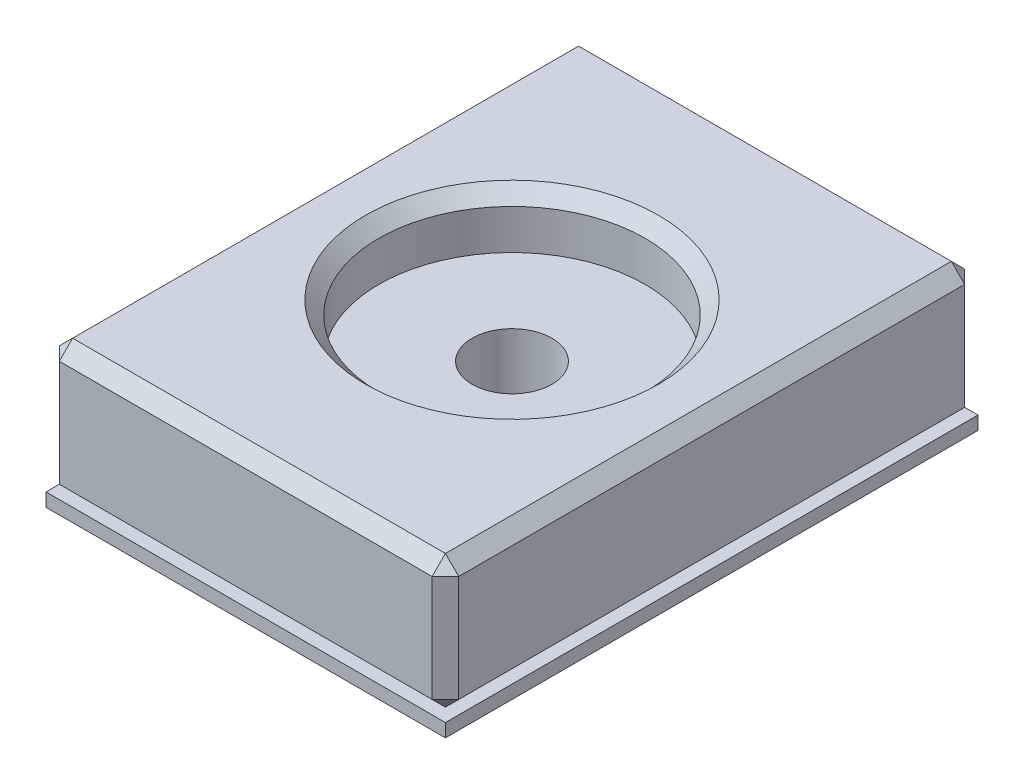
SolidWorks part; units mm, degrees
material "Cedro"
ref_plane "Alzado" through (0, 0, 0) normal (0, 0, 1) x (1, 0, 0)
ref_plane "Planta" through (0, 0, 0) normal (0, 1, 0) x (1, 0, 0)
ref_plane "Vista lateral" through (0, 0, 0) normal (1, 0, 0) x (0, 0, -1)
sketch "Croquis1" plane through (0, 0, 0) normal (0, 0, 1) x (1, 0, 0)
  line L1 (-7.5, -2.5) -> (7.5, -2.5)
  line L2 (-7.5, -2.5) -> (-7.5, 2.5)
  line L3 (-7.5, 2.5) -> (7.5, 2.5)
  line L4 (7.5, -2.5) -> (7.5, 2.5)
  line L5 (-7.5, -2.5) -> (7.5, 2.5) construction
  line L6 (-7.5, 2.5) -> (7.5, -2.5) construction
  point P0 (0, 0)
  dimension "D1" = 5
  dimension "D2" = 15
extrude "Saliente-Extruir1" add sketch "Croquis1" along normal mid plane 20
sketch "Croquis2" plane through (0, 2.5, 0) normal (0, 1, 0) x (1, 0, 0)
  circle A0 centre (0, 0) radius 1.5
  dimension "D1" = 3
extrude "Cortar-Extruir1" cut sketch "Croquis2" against normal through all
sketch "Croquis7" plane through (0, 2.5, 0) normal (0, 1, 0) x (1, 0, 0)
  circle A0 centre (0, 0) radius 5
  circle A1 centre (0, 0) radius 1.5 construction
  dimension "D1" = 10
extrude "Cortar-Extruir3" cut sketch "Croquis7" against normal blind 2
sketch "Croquis3" plane through (0, 0.5, 0) normal (0, 1, 0) x (1, 0, 0)
  line L0 (4, 0) -> (3.4641, 0) construction
  line L1 (-1.7321, -3) -> (1.7321, -3)
  line L2 (1.7321, -3) -> (3.4641, 0)
  line L3 (3.4641, 0) -> (1.7321, 3)
  line L4 (1.7321, 3) -> (-1.7321, 3)
  line L5 (-1.7321, 3) -> (-3.4641, 0)
  line L6 (-3.4641, 0) -> (-1.7321, -3)
  circle A0 centre (0, 0) radius 4
  circle A1 centre (0, 0) radius 3 construction
  dimension "D1" = 3
  dimension "D2" = 8
extrude "Saliente-Extruir2" add sketch "Croquis3" along normal blind 3 separate body
sketch "Croquis4" plane through (0, 3.5, 0) normal (0, 1, 0) x (1, 0, 0)
  circle A0 centre (0, 0) radius 4 construction
  circle A1 centre (0, 0) radius 4
extrude "Saliente-Extruir3" add sketch "Croquis4" along normal blind 6 draft 33
sketch "Croquis5" plane through (0, 9.5, 0) normal (0, 1, 0) x (1, 0, 0)
  line L0 (0, 0) -> (-2.75, 0) construction
  line L1 (0, 0) -> (-2.6027, -0.8879) construction
  line L2 (-2.6027, -0.8879) -> (-1.7264, -0.2864)
  line L3 (-1.7264, -0.2864) -> (-2.75, 0)
  line L4 (-1.7264, -0.2864) -> (0, 0) construction
  line L5 (-2.75, 0) -> (-2.6027, -0.8879) construction
  line L6 (-2.6764, -0.4439) -> (-1.7264, -0.2864)
  line L7 (-1.6936, 0.4406) -> (-2.5123, 1.1185)
  line L8 (-2.7388, 0.2475) -> (-1.6936, 0.4406)
  line L9 (-1.368, 1.0914) -> (-1.8401, 2.0436)
  line L10 (-2.4014, 1.3401) -> (-1.368, 1.0914)
  line L11 (-0.8058, 1.5534) -> (-0.8498, 2.6154)
  line L12 (-1.6487, 2.201) -> (-0.8058, 1.5534)
  line L13 (-0.1043, 1.7469) -> (0.2875, 2.7349)
  line L14 (-0.6109, 2.6813) -> (-0.1043, 1.7469)
  line L15 (0.6152, 1.6383) -> (1.375, 2.3816)
  line L16 (0.5324, 2.698) -> (0.6152, 1.6383)
  line L17 (1.2284, 1.2464) -> (2.2248, 1.6164)
  line L18 (1.5838, 2.2481) -> (1.2284, 1.2464)
  line L19 (1.6291, 0.639) -> (2.6899, 0.5718)
  line L20 (2.3613, 1.4096) -> (1.6291, 0.639)
  line L21 (1.7482, -0.0788) -> (2.6899, -0.5718)
  line L22 (2.7304, 0.3273) -> (1.7482, -0.0788)
  line L23 (1.565, -0.7831) -> (2.2248, -1.6164)
  line L24 (2.6275, -0.8115) -> (1.565, -0.7831)
  line L25 (1.1112, -1.3519) -> (1.375, -2.3816)
  line L26 (2.0703, -1.8101) -> (1.1112, -1.3519)
  line L27 (0.4653, -1.687) -> (0.2875, -2.7349)
  line L28 (1.1551, -2.4957) -> (0.4653, -1.687)
  line L29 (-0.2611, -1.7304) -> (-0.8498, -2.6154)
  line L30 (0.0401, -2.7497) -> (-0.2611, -1.7304)
  line L31 (-0.9424, -1.4746) -> (-1.8401, -2.0436)
  line L32 (-1.0817, -2.5283) -> (-0.9424, -1.4746)
  line L33 (-1.4607, -0.9638) -> (-2.5123, -1.1185)
  line L34 (-2.0166, -1.8697) -> (-1.4607, -0.9638)
  arc A0 (-2.7388, 0.2475) -> (-2.75, 0) centre (0, 0) ccw
  circle A1 centre (0, 0) radius 0.1036 construction
  arc A2 (-2.4014, 1.3401) -> (-2.5123, 1.1185) centre (0, 0) ccw
  arc A3 (-2.0166, -1.8697) -> (-1.8401, -2.0436) centre (0, 0) ccw
  arc A4 (-2.6027, -0.8879) -> (-2.5123, -1.1185) centre (0, 0) ccw
  arc A5 (-1.0817, -2.5283) -> (-0.8498, -2.6154) centre (0, 0) ccw
  arc A6 (0.0401, -2.7497) -> (0.2875, -2.7349) centre (0, 0) ccw
  arc A7 (1.1551, -2.4957) -> (1.375, -2.3816) centre (0, 0) ccw
  arc A8 (2.0703, -1.8101) -> (2.2248, -1.6164) centre (0, 0) ccw
  arc A9 (2.6275, -0.8115) -> (2.6899, -0.5718) centre (0, 0) ccw
  arc A10 (2.7304, 0.3273) -> (2.6899, 0.5718) centre (0, 0) ccw
  arc A11 (2.3613, 1.4096) -> (2.2248, 1.6164) centre (0, 0) ccw
  arc A12 (1.5838, 2.2481) -> (1.375, 2.3816) centre (0, 0) ccw
  arc A13 (0.5324, 2.698) -> (0.2875, 2.7349) centre (0, 0) ccw
  arc A14 (-0.6109, 2.6813) -> (-0.8498, 2.6154) centre (0, 0) ccw
  arc A15 (-1.6487, 2.201) -> (-1.8401, 2.0436) centre (0, 0) ccw
  point P53 (0, 0)
  circle M1 centre (0, 0) radius 0.1036
  dimension "D1" = 1
  dimension "D3" = 15
  dimension "D4" = 5.5
  dimension "D2" = 0.9
extrude "Saliente-Extruir4" add sketch "Croquis5" against normal up to surface (6 mm away) contours L12 A15 L9 L10 A2 L7 L8 A0 L3 L2 A4 L33 L34 A3 L31 L32 A5 L29 L30 A6 L27 L28 A7 L25 L26 A8 L23 L24 A9 L21 L22 A10 L19 L20 A11 L17 L18 A12 L15 L16 A13 L13 L14 A14 L11 M1 up to face at (0, 3.5, 0)
sketch "Croquis6" plane through (0, 3.5, 0) normal (0, -1, 0) x (1, 0, 0)
  circle A0 centre (0, 0) radius 2
  dimension "D1" = 4
extrude "Cortar-Extruir2" cut sketch "Croquis6" against normal blind 2
delete or keep bodies "Sólido-Eliminar1" type delete bodies bodies 106
sketch "Croquis9" plane through (0, -2.5, 0) normal (0, -1, 0) x (1, 0, 0)
  line L4 (-7.5, -10) -> (7.5, -10)
  line L5 (7.5, -10) -> (7.5, 10)
  line L6 (7.5, 10) -> (-7.5, 10)
  line L7 (-7.5, 10) -> (-7.5, -10)
  line L8 (-7.5, -10) -> (7.5, -10)
  line L9 (7.5, -10) -> (7.5, 10)
  line L10 (7.5, 10) -> (-7.5, 10)
  line L11 (-7.5, 10) -> (-7.5, -10)
  circle A0 centre (0, 0) radius 1.5 construction
  circle A1 centre (0, 0) radius 1.5
  dimension "D1" = 0
extrude "Saliente-Extruir5" add sketch "Croquis9" along normal blind 0.5 separate body
chamfer "Chaflán1" distance 0.5 angle 45 13 edges at (-7.5, -2.5, 0) (-7.5, 0, -10) (0, -2.5, -10) (7.5, -2.5, 0) (7.5, 0, -10) (0, -2.5, 10) (-7.5, 0, 10) (7.5, 0, 10) (7.5, 2.5, 0) (0, 2.5, 10) (-7.5, 2.5, 0) (0, 2.5, -10) (0, 2.5, 5)
